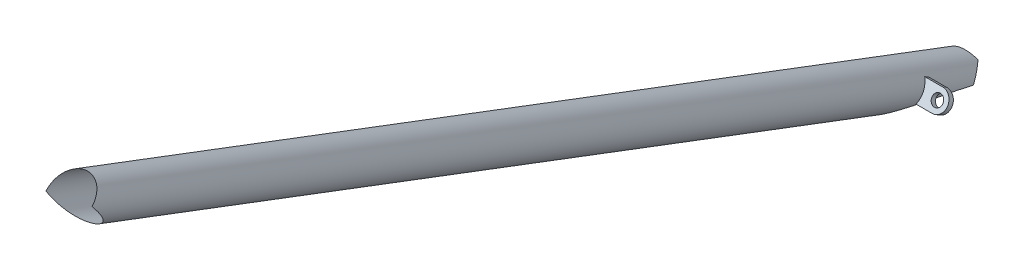
SolidWorks part; units mm, degrees
ref_plane "Front Plane" through (0, 0, 0) normal (0, 0, 1) x (1, 0, 0)
ref_plane "Top Plane" through (0, 0, 0) normal (0, 1, 0) x (1, 0, 0)
ref_plane "Right Plane" through (0, 0, 0) normal (1, 0, 0) x (0, 0, -1)
sketch "Sketch1" plane through (0, 57.7482, 92.8763) normal (0, 0.528, 0.8492) x (1, 0, 0)
  line L0 (-268.4809, -51.9128) -> (-330.3216, 45.1239) construction
  line L1 (-316.8117, 45.1928) -> (-304.1117, 45.1928)
  line L2 (-316.8117, 45.1928) -> (-316.8117, 32.4928)
  line L3 (-316.8117, 32.4928) -> (-304.1117, 32.4928)
  arc A0 (-304.1117, 45.1928) -> (-304.1117, 32.4928) centre (-304.1117, 38.8428) cw
  circle A1 centre (-304.1117, 38.8428) radius 3.429
  point P9 (-305.8187, 38.2925)
  point P13 (-316.8117, 38.8428)
  dimension "D5" = 6.858
  dimension "D6" = 6.35
  dimension "D1" = 12.7
  dimension "D2" = 12.7
  dimension "D3" = 11.43
  dimension "D4" = 8.89
  dimension ".5" = 12.7
extrude "Boss-Extrude1" add sketch "Sketch1" along normal blind 3.175
surface "Surface-Offset1" parameters "D1"=0
